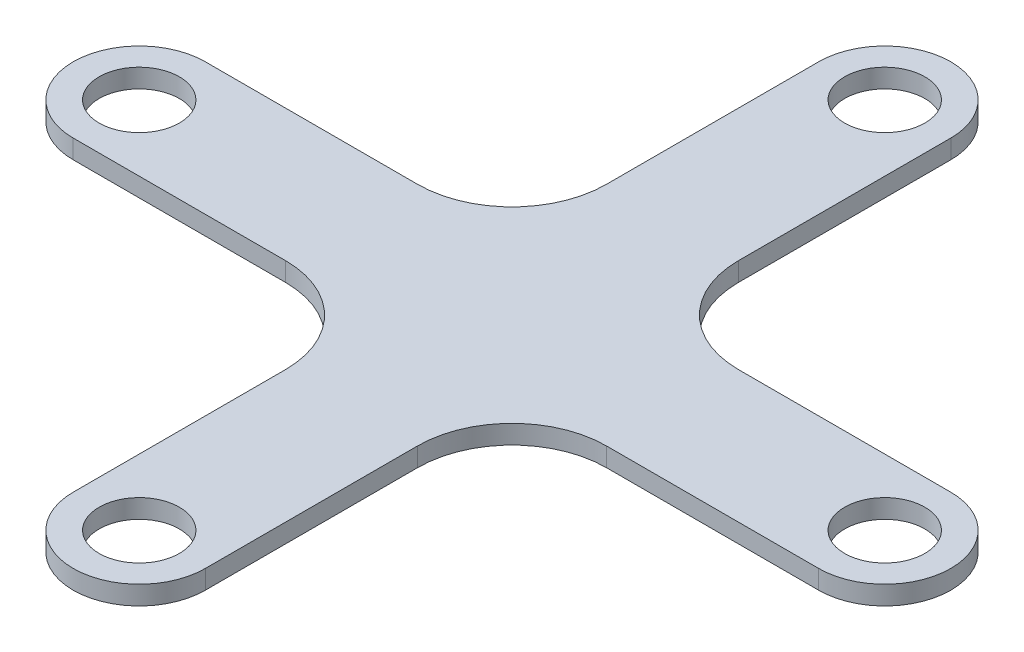
SolidWorks part; units mm, degrees
ref_plane "Front Plane" through (0, 0, 0) normal (0, 0, 1) x (1, 0, 0)
ref_plane "Top Plane" through (0, 0, 0) normal (0, 1, 0) x (1, 0, 0)
ref_plane "Right Plane" through (0, 0, 0) normal (1, 0, 0) x (0, 0, -1)
sketch "Sketch1" plane through (0, 0, 0) normal (0, 1, 0) x (1, 0, 0)
  line L0 (0, -35.5325) -> (0, 57.8061) construction
  line L1 (-52.161, 0) -> (59.9513, 0) construction
  line L2 (-39.5, 7) -> (-17, 7)
  line L3 (-7, 17) -> (-7, 39.5)
  line L4 (17, 7) -> (39.5, 7)
  line L5 (7, 39.5) -> (7, 17)
  line L6 (7, -17) -> (7, -39.5)
  line L7 (39.5, -7) -> (17, -7)
  line L8 (-17, -7) -> (-39.5, -7)
  line L9 (-7, -39.5) -> (-7, -17)
  circle A0 centre (0, 39.5) radius 4.25
  arc A1 (7, 39.5) -> (-7, 39.5) centre (0, 39.5) ccw
  arc A2 (39.5, -7) -> (39.5, 7) centre (39.5, 0) ccw
  circle A3 centre (39.5, 0) radius 4.25
  arc A4 (-7, -39.5) -> (7, -39.5) centre (0, -39.5) ccw
  circle A5 centre (0, -39.5) radius 4.25
  arc A6 (-39.5, 7) -> (-39.5, -7) centre (-39.5, 0) ccw
  circle A7 centre (-39.5, 0) radius 4.25
  arc A8 (-17, 7) -> (-7, 17) centre (-17, 17) ccw
  arc A9 (7, 17) -> (17, 7) centre (17, 17) ccw
  arc A10 (17, -7) -> (7, -17) centre (17, -17) ccw
  arc A11 (-7, -17) -> (-17, -7) centre (-17, -17) ccw
  point P20 (0, 0)
  point P41 (0, 0)
  dimension "D1" = 8.5
  dimension "D2" = 14
  dimension "D4" = 10
  dimension "D6" = 79
  dimension "D3" = 4
  dimension "D5" = 4
extrude "Boss-Extrude1" add sketch "Sketch1" along normal blind 2
